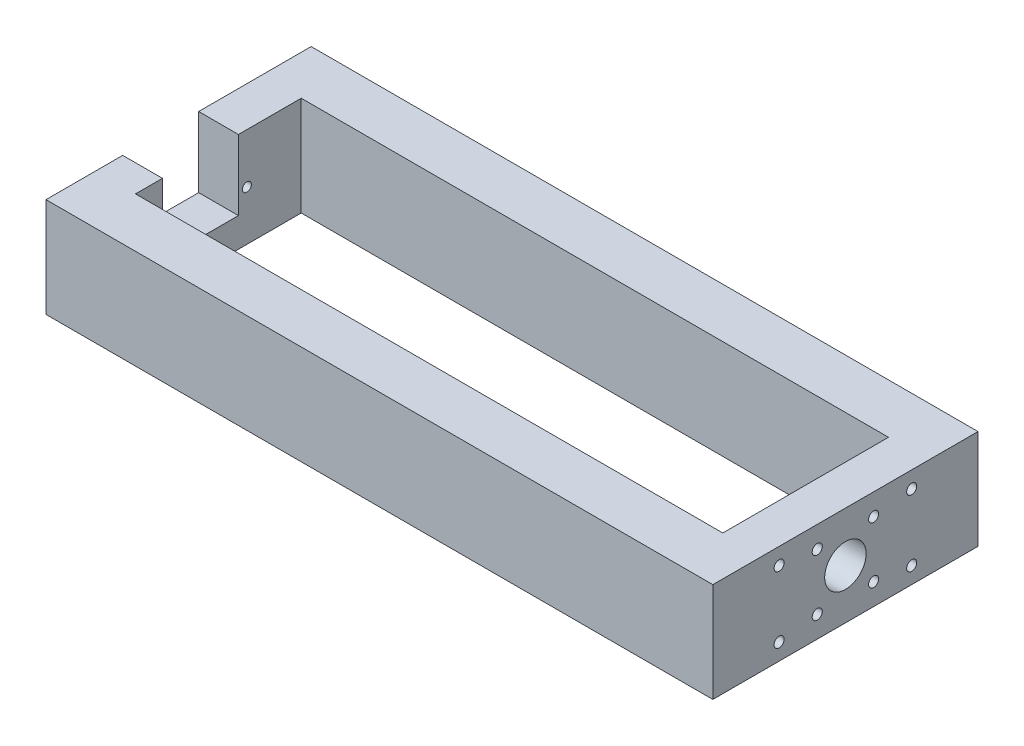
SolidWorks part; units mm, degrees
ref_plane "Front Plane" through (0, 0, 0) normal (0, 0, 1) x (1, 0, 0)
ref_plane "Top Plane" through (0, 0, 0) normal (0, 1, 0) x (1, 0, 0)
ref_plane "Right Plane" through (0, 0, 0) normal (1, 0, 0) x (0, 0, -1)
sketch "Sketch1" plane through (0, 0, 0) normal (0, 1, 0) x (1, 0, 0)
  line L1 (-69.9651, 20.4737) -> (131.2249, 20.4737)
  line L2 (-69.9651, 20.4737) -> (-69.9651, -59.5263)
  line L3 (-69.9651, -59.5263) -> (131.2249, -59.5263)
  line L4 (131.2249, 20.4737) -> (131.2249, -59.5263)
  line L5 (-57.9651, 5.4737) -> (119.2249, 5.4737)
  line L6 (-57.9651, 5.4737) -> (-57.9651, -44.5263)
  line L7 (-57.9651, -44.5263) -> (119.2249, -44.5263)
  line L8 (119.2249, 5.4737) -> (119.2249, -44.5263)
  dimension "D1" = 201.19
  dimension "D2" = 80
  dimension "D3" = 15
  dimension "D4" = 15
  dimension "D5" = 12
  dimension "D6" = 12
extrude "Boss-Extrude1" add sketch "Sketch1" along normal blind 30
sketch "Sketch2" plane through (-69.9651, 0, 0) normal (-1, 0, 0) x (0, 0, 1)
  line L0 (-20.4737, 30) -> (59.5263, 30) construction
  line L1 (13.4663, 30) -> (36.3863, 30)
  line L2 (13.4663, 30) -> (13.4663, 8.8)
  line L3 (13.4663, 8.8) -> (36.3863, 8.8)
  line L4 (36.3863, 30) -> (36.3863, 8.8)
  line L5 (59.5263, 30) -> (59.5263, 0) construction
  circle A0 centre (10.9263, 15) radius 1.35
  circle A1 centre (38.9263, 15) radius 1.35
  dimension "D4" = 2.7
  dimension "D5" = 2.7
  dimension "D6" = 28
  dimension "D7" = 2.54
  dimension "D8" = 6.2
  dimension "D1" = 23.14
  dimension "D2" = 22.92
  dimension "D3" = 21.2
extrude "Cut-Extrude1" cut sketch "Sketch2" against normal blind 30
sketch "Sketch4" plane through (131.2249, 0, 0) normal (1, 0, 0) x (0, 0, -1)
  circle A0 centre (-19.5263, 15) radius 6.25
  circle A1 centre (-28.0263, 23.5) radius 1.52
  circle A2 centre (-11.0263, 23.5) radius 1.52
  circle A3 centre (-11.0263, 6.5) radius 1.52
  circle A4 centre (-28.0263, 6.5) radius 1.52
  circle A5 centre (0.4737, 25) radius 1.52
  circle A6 centre (0.4737, 5) radius 1.52
  circle A7 centre (-39.5263, 5) radius 1.52
  circle A8 centre (-39.5263, 25) radius 1.52
  point P13 (-19.5263, 15)
  point P21 (-19.5263, 15)
  dimension "D1" = 12.5
  dimension "D2" = 3.04
  dimension "D3" = 8.5
  dimension "D4" = 8.5
  dimension "D6" = 3.04
  dimension "D7" = 3.04
  dimension "D8" = 20
  dimension "D9" = 10
  dimension "D10" = 20
  dimension "D5" = 4
  dimension "D11" = 2
extrude "Cut-Extrude2" cut sketch "Sketch4" against normal blind 30
